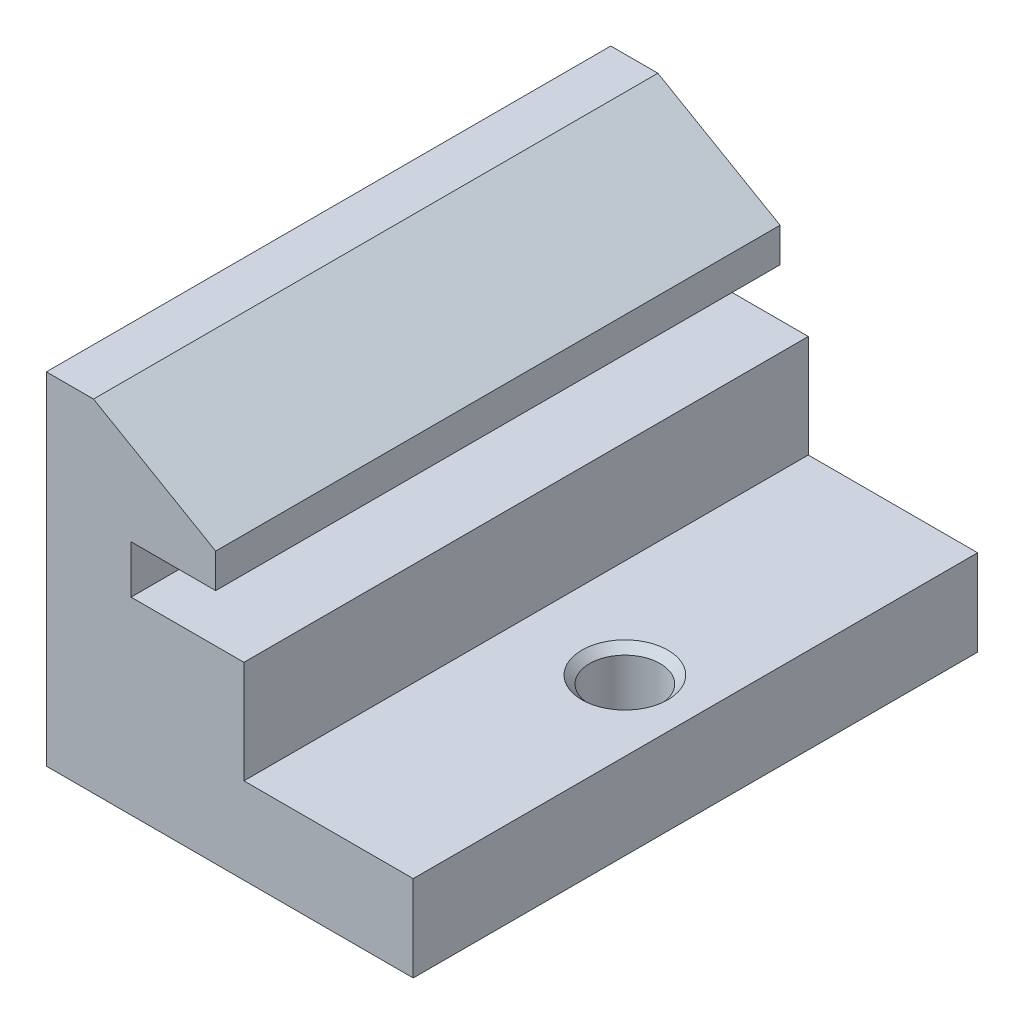
SolidWorks part; units mm, degrees
ref_plane "Front Plane" through (0, 0, 0) normal (0, 0, 1) x (1, 0, 0)
ref_plane "Top Plane" through (0, 0, 0) normal (0, 1, 0) x (1, 0, 0)
ref_plane "Right Plane" through (0, 0, 0) normal (1, 0, 0) x (0, 0, -1)
sketch "Sketch1" plane through (0, 0, 0) normal (0, 0, 1) x (1, 0, 0)
  line L0 (0, 0) -> (4, 0)
  line L1 (0, 0) -> (0, 1.7)
  line L2 (0, 1.7) -> (3, 1.7)
  line L3 (3, 1.7) -> (3, 5.4144)
  line L4 (3, 5.4144) -> (-3, 5.4144)
  line L5 (-3, 5.4144) -> (-3, -6.6882)
  line L6 (-3, -6.6882) -> (10, -6.6882)
  line L7 (10, -6.6882) -> (10, -3.638)
  line L8 (10, -3.638) -> (4, -3.638)
  line L9 (4, -3.638) -> (4, 0)
  dimension "D1" = 1.7
  dimension "D2" = 4
  dimension "D3" = 3
  dimension "D4" = 7
  dimension "D5" = 10
extrude "Boss-Extrude1" add sketch "Sketch1" along normal blind 20
sketch "Sketch2" plane through (0, -3.638, 0) normal (0, 1, 0) x (1, 0, 0)
  line L0 (7.5, -20) -> (7.5, 0) construction
  line L1 (10, -20) -> (4, -20) construction
  line L2 (10, 0) -> (4, 0) construction
  line L4 (10, -20) -> (10, 0) construction
  circle A0 centre (7.5, -10) radius 1.2339
  point P6 (0, 0)
  dimension "D1" = 2.5
hole_wizard "M3x0.5 Tapped Hole1" positions "Sketch3" profile "Sketch4" tap size "M3x0.5" standard "ANSI Metric" end condition through all
sketch "Sketch3" plane through (0, -3.638, 0) normal (0, 1, 0) x (1, 0, 0)
  point P0 (7.5, -10)
sketch "Sketch4" plane through (7.5, -3.638, 10) normal (1, 0, 0) x (0, 0, 1)
  line L0 (0, 0) -> (0, 3.0503)
  line L1 (0, 3.0503) -> (1.25, 3.0503)
  line L2 (1.25, 3.0503) -> (1.25, 0.275)
  line L3 (1.25, 0.275) -> (1.525, 0)
  line L5 (1.525, 0) -> (0, 0)
  line L6 (-1.25, 0.275) -> (-1.525, 0) construction
  line L11 (0, -6.35) -> (0, 107.95) construction
  dimension "Thread Major Dia." = 2.5
  dimension "Thru Tap Drill Depth" = 3.0503
  dimension "Near C'Sink Dia." = 3.05
  dimension "Near C'Sink Angle" = 90
chamfer "Chamfer1" distance 2.5 angle 60 1 edges at (3, 5.4144, 10)
